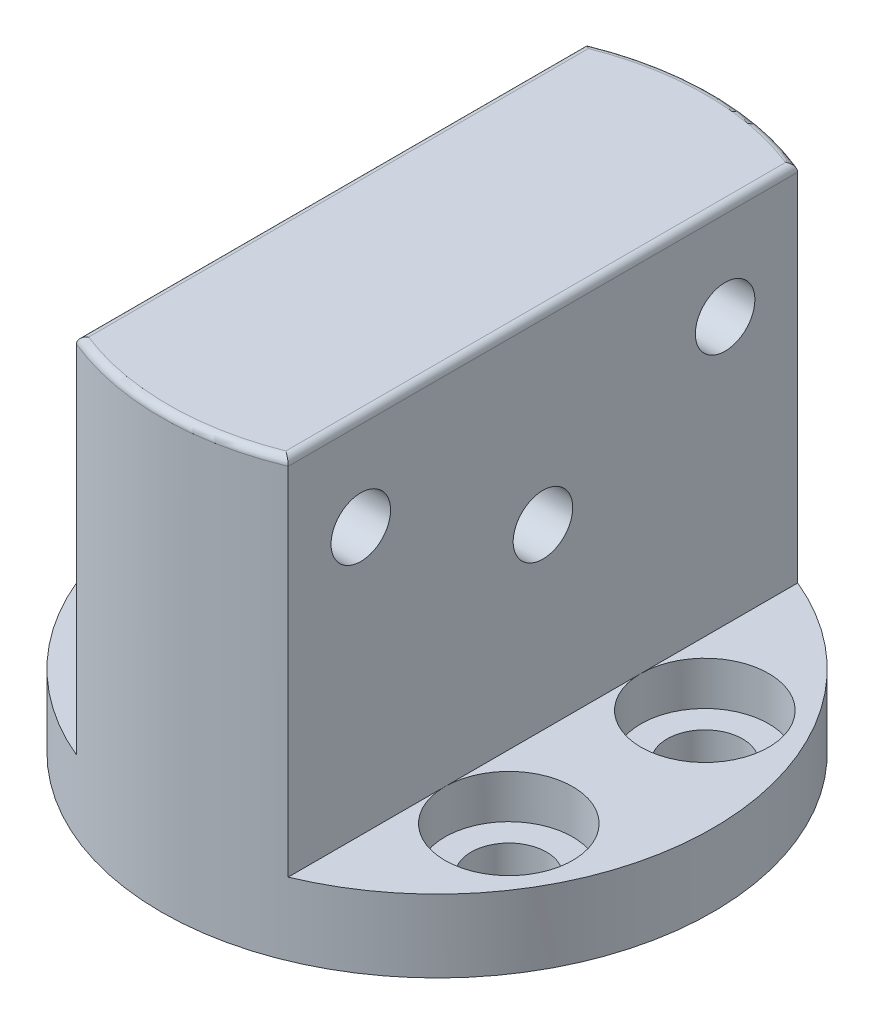
SolidWorks part; units mm, degrees
ref_plane "Front Plane" through (0, 0, 0) normal (0, 0, 1) x (1, 0, 0)
ref_plane "Top Plane" through (0, 0, 0) normal (0, 1, 0) x (1, 0, 0)
ref_plane "Right Plane" through (0, 0, 0) normal (1, 0, 0) x (0, 0, -1)
sketch "Sketch1" plane through (0, 0, 0) normal (0, 1, 0) x (1, 0, 0)
  circle A0 centre (0, 0) radius 19
  circle A1 centre (0, 13.5) radius 2.6 construction
  circle A2 centre (11.6913, 6.75) radius 2.6
  circle A3 centre (11.6913, -6.75) radius 2.6
  circle A4 centre (0, -13.5) radius 2.6 construction
  circle A5 centre (-11.6913, -6.75) radius 2.6
  circle A6 centre (-11.6913, 6.75) radius 2.6
  circle A7 centre (0, 0) radius 13.5 construction
  point P5 (12.3004, 7.6032)
  point P6 (0, 0)
  point P7 (7.7446, 6.9791)
  point P18 (0, 0)
  point P20 (0, 0)
  point P21 (9.7883, 5.6513)
  dimension "D1" = 38
  dimension "D2" = 5.2
  dimension "D4" = 27
  dimension "D3" = 6
extrude "Boss-Extrude1" add sketch "Sketch1" along normal blind 5
sketch "Sketch2" plane through (0, 5, 0) normal (0, 1, 0) x (1, 0, 0)
  circle A0 centre (-11.6913, 6.75) radius 4.4
  circle A1 centre (11.6913, 6.75) radius 4.4
  circle A2 centre (11.6913, -6.75) radius 4.4
  circle A3 centre (-11.6913, -6.75) radius 4.4
  dimension "D1" = 8.8
extrude "Cut-Extrude1" cut sketch "Sketch2" against normal blind 3
sketch "Sketch3" plane through (0, 5, 0) normal (0, 1, 0) x (1, 0, 0)
  line L0 (-7.2913, 17.5453) -> (-7.2913, -17.5453)
  line L1 (7.2913, 17.5453) -> (7.2913, -17.5453)
  circle A0 centre (0, 0) radius 19 construction
  arc A1 (-7.2913, -17.5453) -> (7.2913, -17.5453) centre (0, 0) ccw
  arc A2 (7.2913, 17.5453) -> (-7.2913, 17.5453) centre (0, 0) ccw
  circle A3 centre (-11.6913, 6.75) radius 4.4 construction
  circle A4 centre (11.6913, 6.75) radius 4.4 construction
extrude "Boss-Extrude2" add sketch "Sketch3" along normal blind 25
fillet "Fillet1" radius 0.5 4 edges at (0, 30, -19) (0, 30, 19) (-7.2913, 30, 0) (7.2913, 30, 0)
sketch "Sketch4" plane through (7.2913, 0, 0) normal (1, 0, 0) x (0, 0, -1)
  line L1 (-17.5453, 29.5) -> (-17.5453, 5) construction
  line L2 (-17.5453, 17.25) -> (-17.5453, 29.5) construction
  line L3 (17.5453, 29.5) -> (7.5453, 29.5) construction
  line L8 (17.5453, 29.5) -> (-17.5453, 29.5) construction
  line L9 (-17.5453, 29.5) -> (-7.5453, 29.5) construction
  circle A0 centre (-12.5453, 23.375) radius 2.05
  circle A1 centre (12.5453, 23.375) radius 2.05
  circle A2 centre (0, 17.25) radius 2.05
  point P6 (12.5453, 29.5)
  point P9 (-12.5453, 29.5)
  point P15 (-17.5453, 23.375)
  dimension "D1" = 4.1
  dimension "D2" = 10
extrude "Cut-Extrude2" cut sketch "Sketch4" against normal through all
